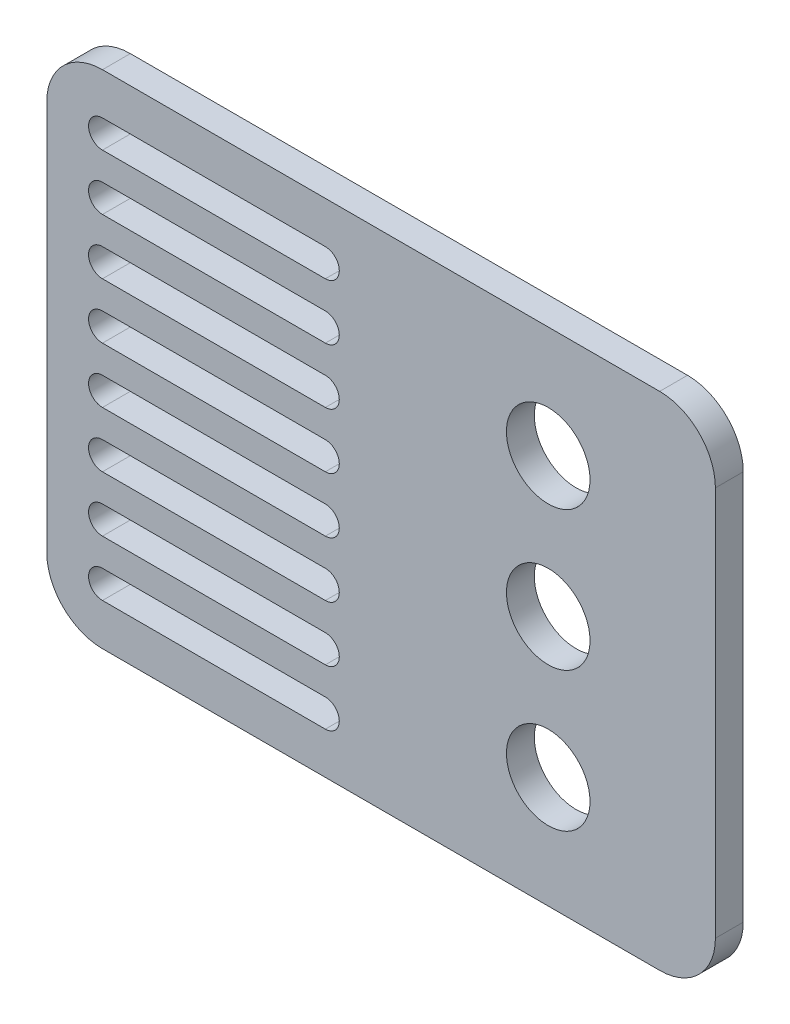
SolidWorks part; units mm, degrees
material "6061 Alloy"
ref_plane "Front Plane" through (0, 0, 0) normal (0, 0, 1) x (1, 0, 0)
ref_plane "Top Plane" through (0, 0, 0) normal (0, 1, 0) x (1, 0, 0)
ref_plane "Right Plane" through (0, 0, 0) normal (1, 0, 0) x (0, 0, -1)
sketch "Sketch2" plane through (0, 0, 0) normal (0, 0, 1) x (1, 0, 0)
  line L1 (76.2, -57.15) -> (-76.2, -57.15)
  line L2 (76.2, -57.15) -> (76.2, 57.15)
  line L3 (76.2, 57.15) -> (-76.2, 57.15)
  line L4 (-76.2, -57.15) -> (-76.2, 57.15)
  line L5 (76.2, -57.15) -> (-76.2, 57.15) construction
  line L6 (76.2, 57.15) -> (-76.2, -57.15) construction
  point P0 (0, 0)
  dimension "D1" = 152.4
  dimension "D2" = 114.3
extrude "Base Extrude" add sketch "Sketch2" along normal blind 6.35
fillet "Fillet" radius 12.7 4 edges at (-76.2, -57.15, 3.175) (76.2, -57.15, 3.175) (-76.2, 57.15, 3.175) (76.2, 57.15, 3.175)
sketch "Sketch3" plane through (0, 0, 6.35) normal (0, 0, 1) x (1, 0, 0)
  line L0 (76.2, -44.45) -> (76.2, 44.45) construction
  line L1 (63.5, 57.15) -> (-63.5, 57.15) construction
  circle A0 centre (38.1, 31.75) radius 9.525
  dimension "D1" = 38.1
  dimension "D2" = 25.4
extrude "Circular Cut" cut sketch "Sketch3" against normal through all
sketch "Sketch5" plane through (0, 0, 6.35) normal (0, 0, 1) x (1, 0, 0)
  line L0 (-63.5, 44.45) -> (-12.7, 44.45) construction
  line L1 (-63.5, 47.625) -> (-12.7, 47.625)
  line L2 (-63.5, 41.275) -> (-12.7, 41.275)
  line L3 (63.5, 57.15) -> (-63.5, 57.15) construction
  line L4 (-76.2, 44.45) -> (-76.2, -44.45) construction
  arc A0 (-63.5, 47.625) -> (-63.5, 41.275) centre (-63.5, 44.45) ccw
  arc A1 (-12.7, 41.275) -> (-12.7, 47.625) centre (-12.7, 44.45) ccw
  point P2 (-38.1, 44.45)
  dimension "D1" = 50.8
  dimension "D2" = 6.35
  dimension "D3" = 12.7
  dimension "D4" = 12.7
extrude "Slot Cut" cut sketch "Sketch5" against normal through all
pattern_linear "Slot LPattern" count 8 spacing 12.7 along (0, -1, 0) of "Slot Cut"
pattern_linear "Circle LPattern" count 3 spacing 31.75 along (0, -1, 0) of "Circular Cut"
